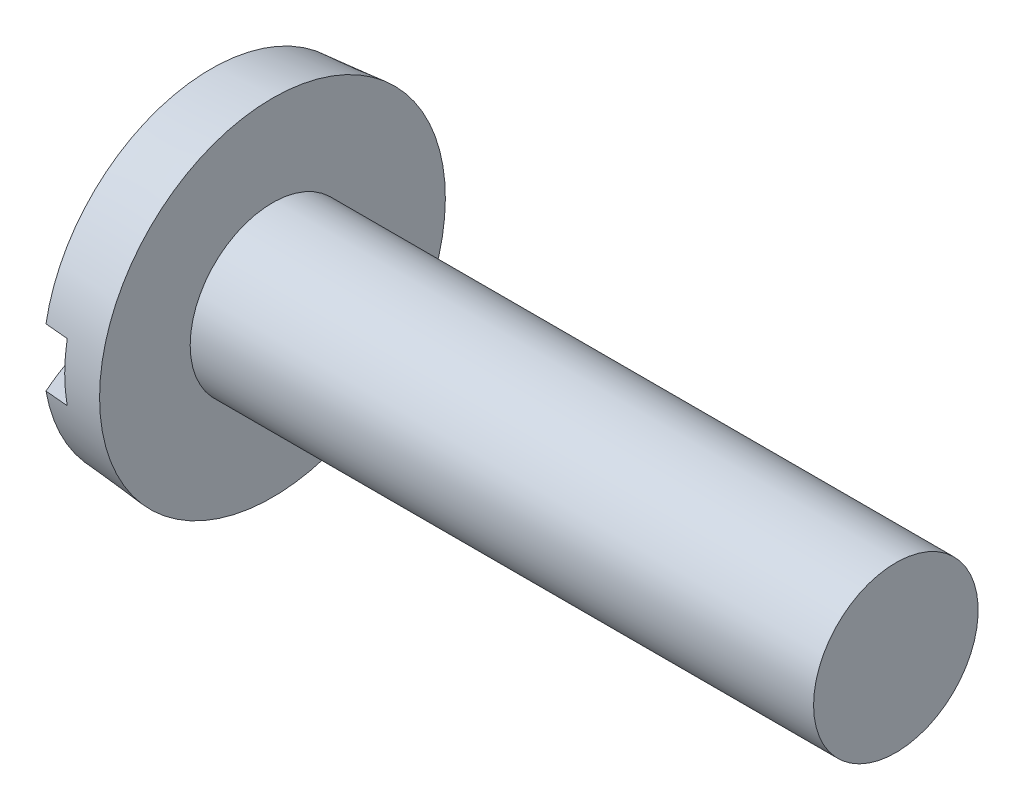
SolidWorks part; units mm, degrees
ref_plane "Plane1" through (0, 0, 0) normal (0, 0, 1) x (1, 0, 0)
ref_plane "Plane2" through (0, 0, 0) normal (0, 1, 0) x (1, 0, 0)
ref_plane "Plane3" through (0, 0, 0) normal (1, 0, 0) x (0, 0, -1)
sketch "BodySke" plane through (0, 0, 0) normal (0, 0, 1) x (1, 0, 0)
  line L0 (1.4986, 1.2573) -> (1.4986, 2.6416)
  line L1 (1.4986, 2.6416) -> (0.5588, 2.5594)
  line L2 (-25.4, 0) -> (127, 0) construction
  line L3 (1.4986, -2.6416) -> (0.5588, -2.5594) construction
  line L4 (1.4986, 1.2573) -> (11.0236, 1.2573)
  line L5 (11.0236, 1.2573) -> (11.0236, 0)
  line L6 (11.0236, 0) -> (0, 0)
  line L7 (1.4986, -1.2573) -> (11.0236, -1.2573) construction
  line L8 (2.0269, 6.35) -> (2.0269, -3.175) construction
  line L9 (1.4986, 6.35) -> (1.4986, -3.175) construction
  arc A0 (0, 0) -> (0.5588, 2.5594) centre (6.1405, 0) cw
  dimension "Head_ang" = 85
  dimension "Oval_ht" = 0.5588
  dimension "Head_ht" = 1.4986
  dimension "Diameter" = 2.5146
  dimension "Length" = 9.525
  dimension "Head_dia" = 5.2832
  dimension "Advance" = 0.5283
  dimension "Thread_nom" = 9.525
revolve "Base-Revolve" add sketch "BodySke" angle 360 about L2
cosmetic thread "ThreadCosmetic" [suppressed] parameters "Thread_length"=8.9967, "Thread_minor"=1.8821
sketch "Sketch2" plane through (0, 0, 0) normal (1, 0, 0) x (0, 0, -1)
  line L0 (2.6416, -0.4445) -> (2.6416, 0.4445)
  line L1 (2.6416, 0.4445) -> (-2.6416, 0.4445)
  line L2 (-2.6416, 0.4445) -> (-2.6416, -0.4445)
  line L3 (-2.6416, -0.4445) -> (2.6416, -0.4445)
  dimension "D1" = 5.2832
  dimension "D2" = 2.6416
  dimension "D3" = 0.4445
  dimension "Slot_width" = 0.889
extrude "Slot" cut sketch "Sketch2" along normal blind 0.9144
sketch "Sketch3" plane through (0, 0, 0) normal (1, 0, 0) x (0, 0, -1)
  line L0 (-0.3937, 1.7272) -> (0.3937, 1.7272)
  line L1 (0.3937, 1.7272) -> (0.3937, -1.7272)
  line L2 (0.3937, -1.7272) -> (-0.3937, -1.7272)
  line L3 (-0.3937, -1.7272) -> (-0.3937, 1.7272)
  dimension "Cross_width" = 0.7874
  dimension "D1" = 0.3937
  dimension "Cross_dia" = 3.4544
  dimension "D2" = 1.7272
ref_plane "Plane4" through (1.9558, 0, 0) normal (1, 0, 0) x (0, 0, -1)
sketch "Sketch4" plane through (1.9558, 0, 0) normal (1, 0, 0) x (0, 0, -1)
  line L0 (-0.1968, 0.1968) -> (0.1968, 0.1968)
  line L1 (0.1968, 0.1968) -> (0.1969, -0.1968)
  line L2 (0.1969, -0.1968) -> (-0.1968, -0.1969)
  line L3 (-0.1968, -0.1969) -> (-0.1968, 0.1968)
  dimension "D1" = 0.3937
  dimension "D2" = 0.1968
  dimension "D3" = 0.3937
  dimension "D4" = 0.1968
loft "Cross" [suppressed] cut profiles "Sketch3", "Sketch4"
pattern_circular "CirPattern1" [suppressed] count 2 every 90 about axis through (-25.4, 0, 0) along (1, 0, 0)
sketch "ThdSchSke" plane through (0, 0, 0) normal (0, 0, 1) x (1, 0, 0)
  line L0 (2.0269, -0.9411) -> (1.8055, -1.2573)
  line L1 (2.0269, -0.9411) -> (2.2483, -1.2573)
  line L2 (2.2483, -1.2573) -> (2.2483, -1.5716)
  line L3 (-3.175, 0) -> (5.1513, 0) construction
  line L5 (2.2483, -1.5716) -> (1.8055, -1.5716)
  line L6 (1.8055, -1.5716) -> (1.8055, -1.2573)
  dimension "Diameter" = 2.5146
  dimension "SideAngle" = 55
  dimension "VeeAngle" = 70
  dimension "Thread_minor" = 1.8821
  dimension "Overcut" = 3.1432
  dimension "Start" = 2.0269
revolve "ThreadSchematic" [suppressed] cut sketch "ThdSchSke" angle 360 about L3
pattern_linear "ThdSchPat" [suppressed]
equation "\"D1@Sketch3\" = \"Cross_width@Sketch3\" / 2"
equation "\"D2@Sketch3\" = \"Cross_dia@Sketch3\" / 2"
equation "\"D1@Sketch4\" = \"Cross_width@Sketch3\"*.5"
equation "\"D2@Sketch4\" = \"D1@Sketch4\" / 2"
equation "\"D3@Sketch4\" = \"D1@Sketch4\""
equation "\"D4@Sketch4\" = \"D2@Sketch4\""
equation "\"D1@Sketch2\" = \"Head_dia@BodySke\""
equation "\"D2@Sketch2\" = \"D1@Sketch2\" / 2"
equation "\"D3@Sketch2\" = \"Slot_width@Sketch2\" / 2"
equation "\"Thread_length@ThreadCosmetic\" = ((sgn( (\"Length@BodySke\" - \"Advance@BodySke\" ) - \"Thread_nom@BodySke\" )-1)*( (\"Length@BodySke\" - \"Advance@BodySke\" ) - \"Thread_nom@BodySke\" ))/-2+ \"Thread_nom@BodySke\""
equation "\"Thread_minor@ThdSchSke\" = \"Thread_minor@ThreadCosmetic\""
equation "\"Diameter@ThdSchSke\" = \"Diameter@BodySke\""
equation "\"Overcut@ThdSchSke\" = \"Diameter@BodySke\" * 1.25"
equation "\"Start@ThdSchSke\" = \"Head_ht@BodySke\" + \"Length@BodySke\" - \"Thread_length@ThreadCosmetic\"  '---Non-countersunk---"
equation "\"Num_threads@ThdSchPat\" = int( \"Thread_length@ThreadCosmetic\" / \"Advance@BodySke\" + 0.999 )  + 1"
equation "\"Advance@ThdSchPat\" = \"Thread_length@ThreadCosmetic\" /  (\"Num_threads@ThdSchPat\" - 1) 'relax it"
